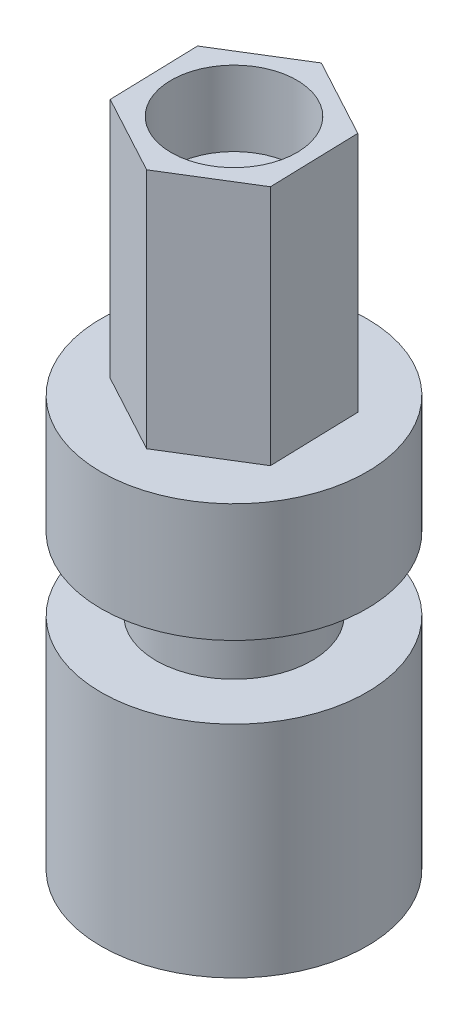
SolidWorks part; units mm, degrees
ref_plane "Front Plane" through (0, 0, 0) normal (0, 0, 1) x (1, 0, 0)
ref_plane "Top Plane" through (0, 0, 0) normal (0, 1, 0) x (1, 0, 0)
ref_plane "Right Plane" through (0, 0, 0) normal (1, 0, 0) x (0, 0, -1)
sketch "Sketch1" plane through (0, 0, 0) normal (0, 1, 0) x (1, 0, 0)
  circle A0 centre (0, 0) radius 3.5
  dimension "D1" = 7
extrude "Boss-Extrude1" add sketch "Sketch1" along normal blind 1
sketch "Sketch2" plane through (0, 1, 0) normal (0, 1, 0) x (1, 0, 0)
  circle A0 centre (0, 0) radius 5.5
  dimension "D1" = 11
extrude "Boss-Extrude2" add sketch "Sketch2" along normal blind 8 contours A0
sketch "Sketch3" plane through (0, 9, 0) normal (0, 1, 0) x (1, 0, 0)
  circle A0 centre (0, 0) radius 5.5
extrude "Boss-Extrude3" add sketch "Sketch3" along normal blind 9
sketch "Sketch4" plane through (0, 18, 0) normal (0, 1, 0) x (1, 0, 0)
  line L1 (3.2772, -1.7684) -> (3.1701, 1.954)
  line L2 (3.1701, 1.954) -> (-0.1071, 3.7224)
  line L3 (-0.1071, 3.7224) -> (-3.2772, 1.7684)
  line L4 (-3.2772, 1.7684) -> (-3.1701, -1.954)
  line L5 (-3.1701, -1.954) -> (0.1071, -3.7224)
  line L6 (0.1071, -3.7224) -> (3.2772, -1.7684)
  circle A0 centre (0, 0) radius 3.225 construction
  dimension "D1" = 6.45
extrude "Boss-Extrude5" add sketch "Sketch4" along normal blind 10
sketch "Sketch5" plane through (0, 28, 0) normal (0, 1, 0) x (1, 0, 0)
  circle A0 centre (0, 0) radius 1.5
  dimension "D1" = 3
extrude "Cut-Extrude1" cut sketch "Sketch5" against normal through all
sketch "Sketch6" plane through (0, 0, 0) normal (0, -1, 0) x (1, 0, 0)
  circle A0 centre (0, 0) radius 2.6
  dimension "D1" = 5.2
extrude "Cut-Extrude2" cut sketch "Sketch6" against normal blind 3.1
ref_plane "Plane3" through (0, 10.1, 0) normal (0, 1, 0) x (1, 0, 0)
ref_point "Point1"
sketch "Sketch7" plane through (0, 10.1, 0) normal (0, 1, 0) x (1, 0, 0)
  circle A0 centre (0, 0) radius 3.225
  circle A1 centre (0, 0) radius 8.6762
  dimension "D1" = 6.45
extrude "Cut-Extrude3" cut sketch "Sketch7" along normal blind 3 contours A0 | A1
sketch "Sketch8" plane through (0, 28, 0) normal (0, 1, 0) x (1, 0, 0)
  circle A0 centre (0, 0) radius 2.6
  dimension "D1" = 5.2
extrude "Cut-Extrude4" cut sketch "Sketch8" against normal blind 3.1
